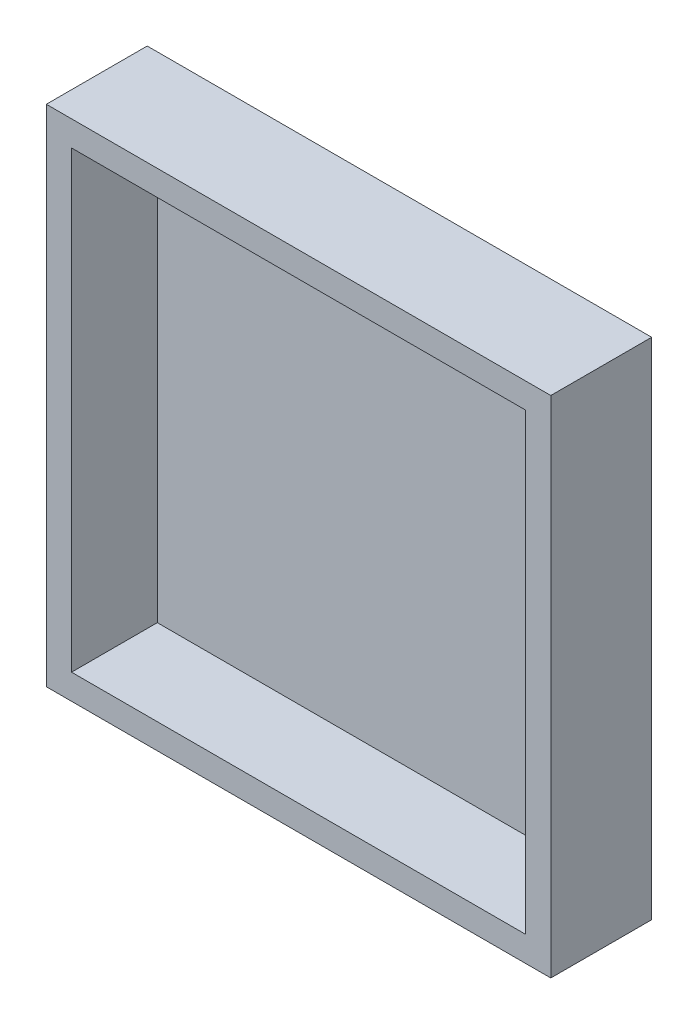
SolidWorks part; units mm, degrees
ref_plane "Front Plane" through (0, 0, 0) normal (0, 0, 1) x (1, 0, 0)
ref_plane "Top Plane" through (0, 0, 0) normal (0, 1, 0) x (1, 0, 0)
ref_plane "Right Plane" through (0, 0, 0) normal (1, 0, 0) x (0, 0, -1)
sketch "Sketch1" plane through (0, 0, 0) normal (0, 0, 1) x (1, 0, 0)
  line L1 (-63.5, -63.5) -> (63.5, -63.5)
  line L2 (-63.5, -63.5) -> (-63.5, 63.5)
  line L3 (-63.5, 63.5) -> (63.5, 63.5)
  line L4 (63.5, -63.5) -> (63.5, 63.5)
  line L5 (-63.5, -63.5) -> (63.5, 63.5) construction
  line L6 (-63.5, 63.5) -> (63.5, -63.5) construction
  point P0 (0, 0)
  dimension "D1" = 127
  dimension "D2" = 127
extrude "Boss-Extrude1" add sketch "Sketch1" along normal blind 25.4 contours L2 L1 L4 L3
sketch "Sketch2" plane through (0, 0, 25.4) normal (0, 0, 1) x (1, 0, 0)
  line L1 (-57.15, -57.15) -> (57.15, -57.15)
  line L2 (-57.15, -57.15) -> (-57.15, 57.15)
  line L3 (-57.15, 57.15) -> (57.15, 57.15)
  line L4 (57.15, -57.15) -> (57.15, 57.15)
  line L5 (-57.15, -57.15) -> (57.15, 57.15) construction
  line L6 (-57.15, 57.15) -> (57.15, -57.15) construction
  point P0 (0, 0)
  dimension "D1" = 114.3
  dimension "D2" = 114.3
extrude "Cut-Extrude1" cut sketch "Sketch2" against normal blind 21.59
